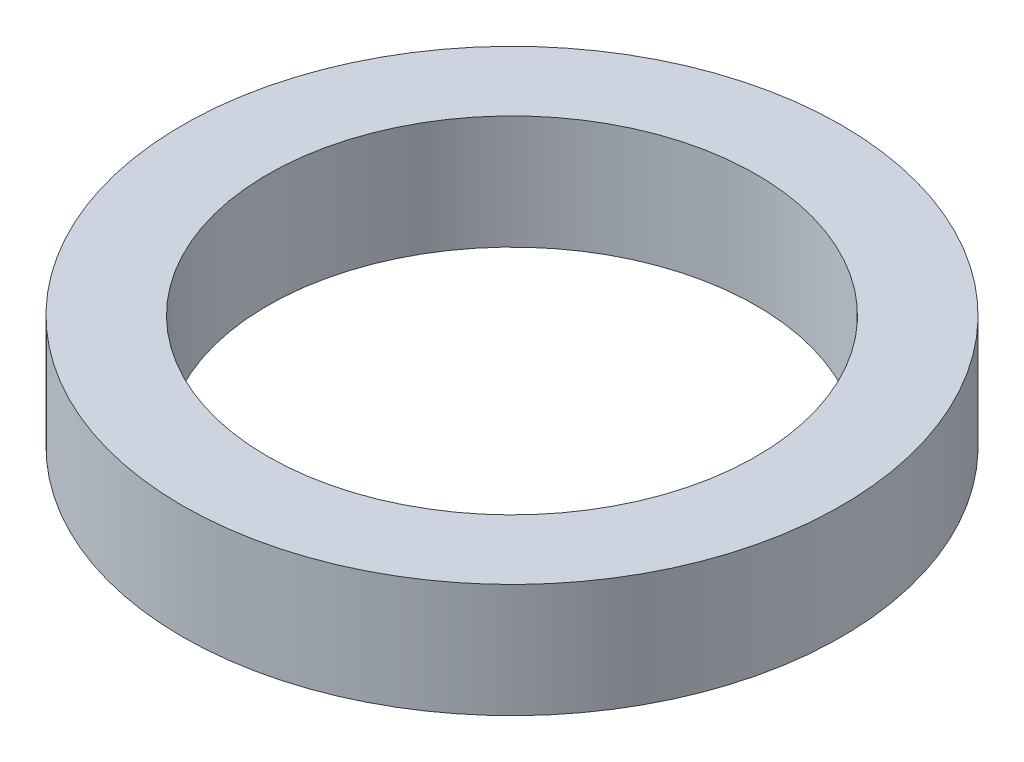
SolidWorks part; units mm, degrees
ref_plane "Front Plane" through (0, 0, 0) normal (0, 0, 1) x (1, 0, 0)
ref_plane "Top Plane" through (0, 0, 0) normal (0, 1, 0) x (1, 0, 0)
ref_plane "Right Plane" through (0, 0, 0) normal (1, 0, 0) x (0, 0, -1)
sketch "Sketch1" plane through (0, 0, 0) normal (0, 1, 0) x (1, 0, 0)
  circle A0 centre (0, 0) radius 21.5
  circle A1 centre (0, 0) radius 29
  dimension "D1" = 43
  dimension "D2" = 58
extrude "Boss-Extrude1" add sketch "Sketch1" along normal blind 10
